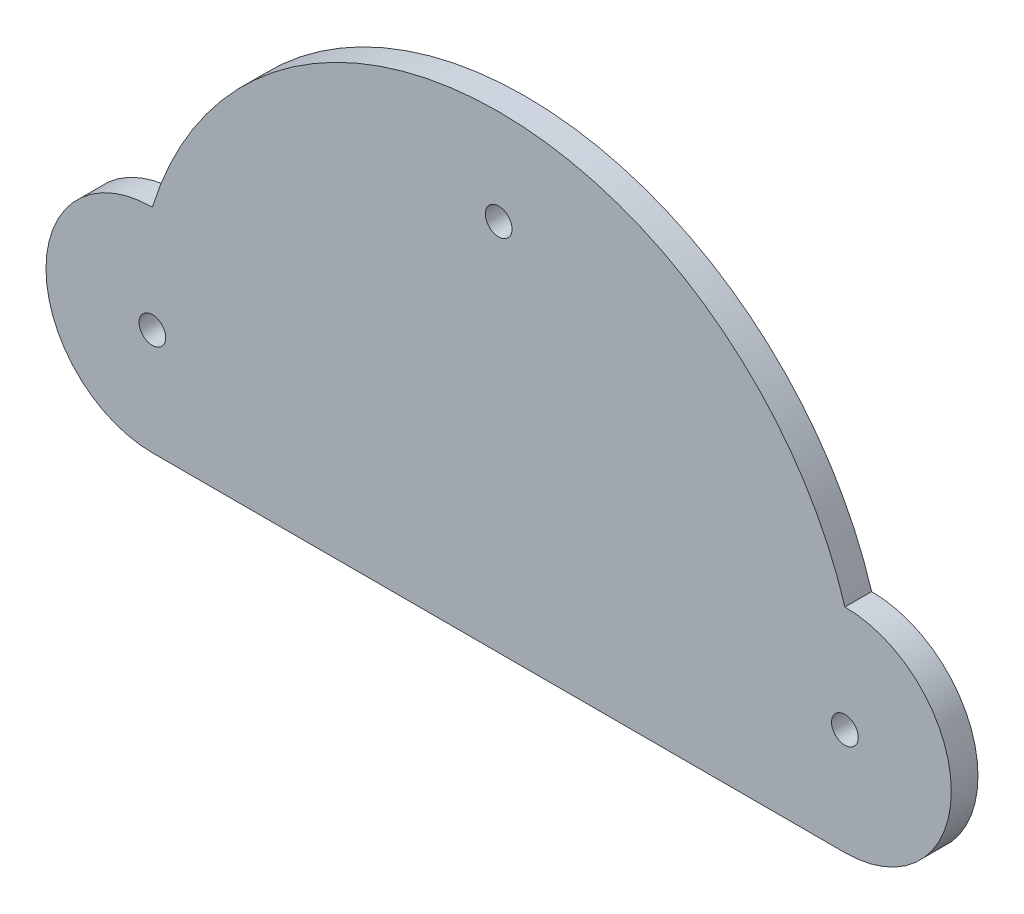
SolidWorks part; units mm, degrees
ref_plane "Alzado" through (0, 0, 0) normal (0, 0, 1) x (1, 0, 0)
ref_plane "Planta" through (0, 0, 0) normal (0, 1, 0) x (1, 0, 0)
ref_plane "Vista lateral" through (0, 0, 0) normal (1, 0, 0) x (0, 0, -1)
sketch "Croquis1" plane through (0, 0, 0) normal (0, 0, 1) x (1, 0, 0)
  line L0 (0, 0) -> (77.78, 0) construction
  line L2 (0, -11.9477) -> (77.78, -11.9477)
  arc A0 (0, 11.9477) -> (0, -11.9477) centre (0, 0) ccw
  arc A1 (77.78, -11.9477) -> (77.78, 11.9477) centre (77.78, 0) ccw
  circle A2 centre (0, 0) radius 1.5
  circle A3 centre (77.78, 0) radius 1.5
  circle A4 centre (38.89, 30) radius 1.5
  arc A5 (77.78, 11.9477) -> (0, 11.9477) centre (38.89, 0) ccw
  point P3 (38.89, 0)
  dimension "D2" = 3
  dimension "D3" = 3
  dimension "D5" = 3
  dimension "D1" = 77.78
  dimension "D4" = 30
extrude "Saliente-Extruir1" add sketch "Croquis1" along normal blind 3
